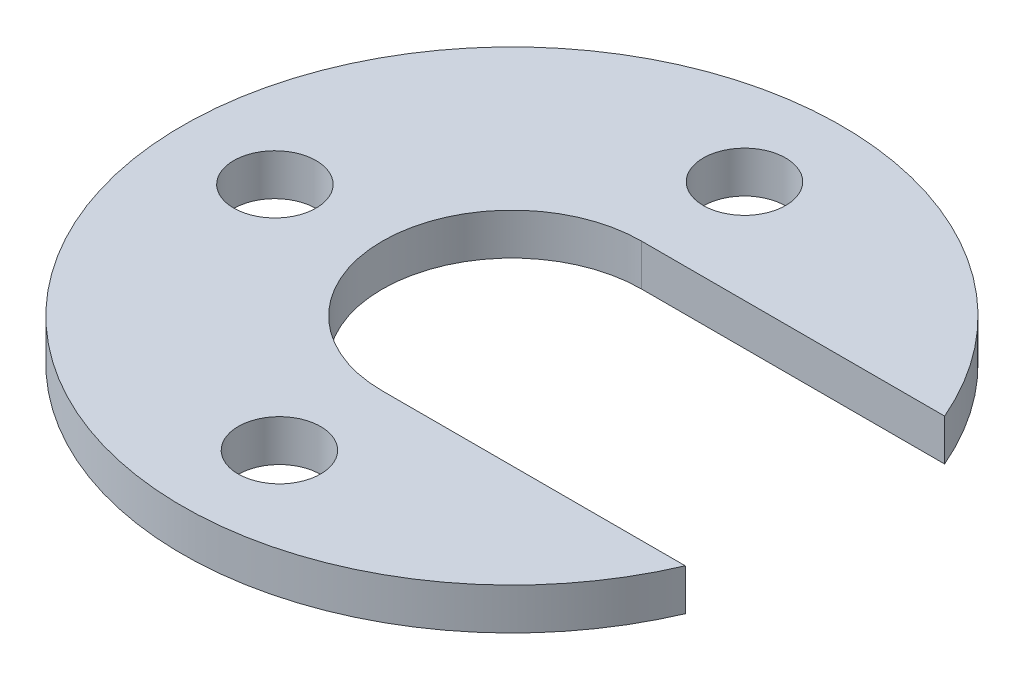
SolidWorks part; units mm, degrees
ref_plane "Ön Düzlem" through (0, 0, 0) normal (0, 0, 1) x (1, 0, 0)
ref_plane "Üst Düzlem" through (0, 0, 0) normal (0, 1, 0) x (1, 0, 0)
ref_plane "Sağ Düzlem" through (0, 0, 0) normal (1, 0, 0) x (0, 0, -1)
sketch "Çizim1" plane through (0, 0, 0) normal (0, 1, 0) x (1, 0, 0)
  line L0 (0, 0) -> (39.6863, 0) construction
  line L1 (0, 15.613) -> (36.4861, 15.613)
  line L2 (0, -15.613) -> (36.4861, -15.613)
  circle A0 centre (0, 0) radius 39.6863
  arc A1 (0, 15.613) -> (0, -15.613) centre (0, 0) ccw
  circle A3 centre (-28, -0.5443) radius 4.9608
  circle A4 centre (0, 28) radius 4.9608
  circle A5 centre (0, -28) radius 4.9608
  point P3 (19.8432, 0)
  point P15 (0, 0)
  point P16 (0, 0)
  point P17 (0, 0)
  point P18 (0, 0)
  point P19 (0, 0)
  point P20 (-0.0564, 27.1597)
  dimension "D1" = 28
  dimension "D2" = 28
  dimension "D3" = 28
  dimension "D4" = 28
extrude "Yükseklik-Ekstrüzyon1" add sketch "Çizim1" along normal blind 5 contours A1 L1 A0 L2 A5 A4 A3
